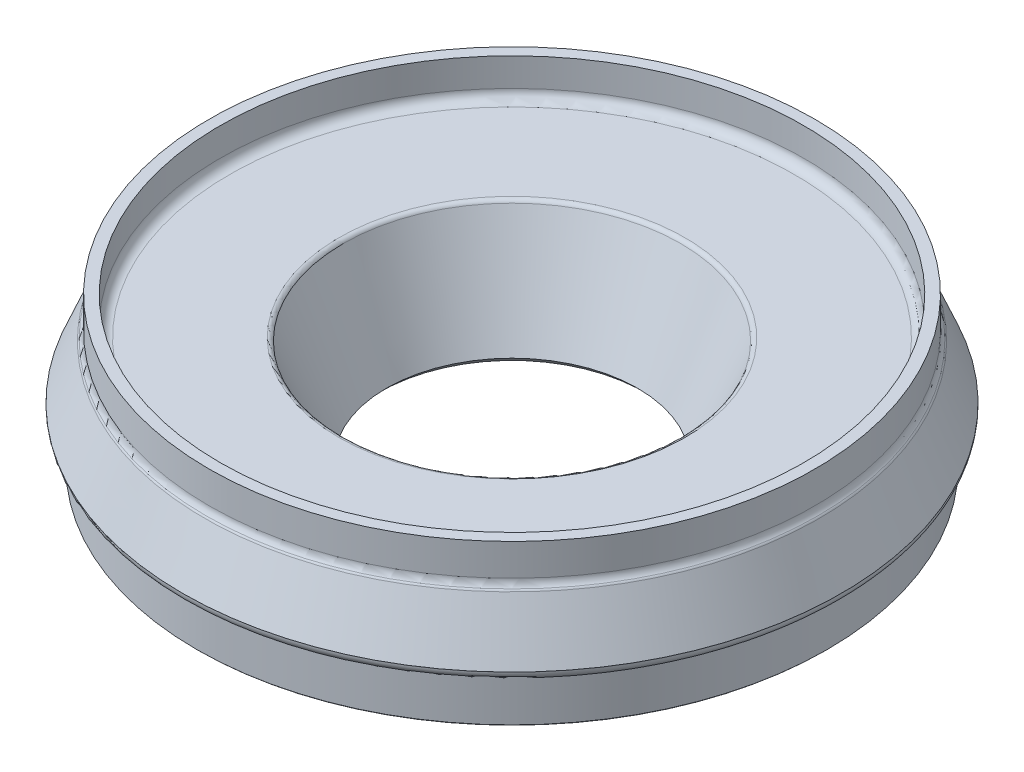
SolidWorks part; units mm, degrees
material "PC 高粘度"
ref_plane "前视基准面" through (0, 0, 0) normal (0, 0, 1) x (1, 0, 0)
ref_plane "上视基准面" through (0, 0, 0) normal (0, 1, 0) x (1, 0, 0)
ref_plane "右视基准面" through (0, 0, 0) normal (1, 0, 0) x (0, 0, -1)
sketch "草图2" plane through (0, 0, 0) normal (0, 0, 1) x (1, 0, 0)
  line L0 (0, 0) -> (1.695, 0)
  line L1 (1.695, 0) -> (1.695, 0.6017)
  line L2 (1.4461, 1.2033) -> (0, 1.2033)
  line L3 (1.695, 0) -> (-0.5, 0)
  line L4 (-0.5, 0) -> (0, 0)
  line L5 (0, 1.2033) -> (-0.5, 0)
  line L6 (1.4461, 1.2033) -> (1.695, 0.6017)
  line L7 (-1.805, 0) -> (-1.805, 1.6213)
  dimension "D1" = 1.695
  dimension "D2" = 0.5
  dimension "D3" = 3.5
  dimension "D4" = 1.2033
revolve "旋转1" add sketch "草图2" angle 360 about L7
ref_plane "基准面1" through (0, 0.5, 0) normal (0, 1, 0) x (1, 0, 0)
sketch "草图3" plane through (0, 0.5, 0) normal (0, 1, 0) x (1, 0, 0)
  circle A0 centre (-1.805, 0) radius 3.5
  circle A1 centre (-1.805, 0) radius 3.25
ref_plane "基准面2" through (0, 0.25, 0) normal (0, 1, 0) x (1, 0, 0)
sketch "草图5" plane through (0, 0.25, 0) normal (0, 1, 0) x (1, 0, 0)
  circle A0 centre (-1.805, 0) radius 3.25
  circle A1 centre (-1.805, 0) radius 3
fillet "圆角2" radius 0.05 2 edges at (-1.805, 1.2033, -3.2511) (-1.805, 1.2033, -1.805)
sketch "草图6" plane through (0, 1.2033, 0) normal (0, 1, 0) x (1, 0, 0)
  circle A0 centre (-1.805, 0) radius 3.2177
  circle A1 centre (-1.805, 0) radius 3.1
extrude "凸台-拉伸1" add sketch "草图6" along normal blind 0.4
fillet "圆角4" radius 0.1 2 edges at (-1.805, 1.2033, 3.1) (-1.805, 1.2033, 3.2177)
chamfer "倒角1" distance 0.1 angle 45 1 edges at (-1.805, 0, -1.305)
sketch "草图7" plane through (0, 0.5, 0) normal (0, 1, 0) x (1, 0, 0)
  circle A0 centre (-1.805, 0) radius 3.5
  circle A1 centre (-1.805, 0) radius 3.35
extrude "切除-拉伸3" cut sketch "草图7" against normal blind 0.5
chamfer "倒角2" distance 0.01 angle 45 2 edges at (-1.805, 0.5, 3.35) (-1.805, 0, 3.35)
fillet "圆角6" radius 0.1 1 edges at (-1.805, 0.5, 3.5)
